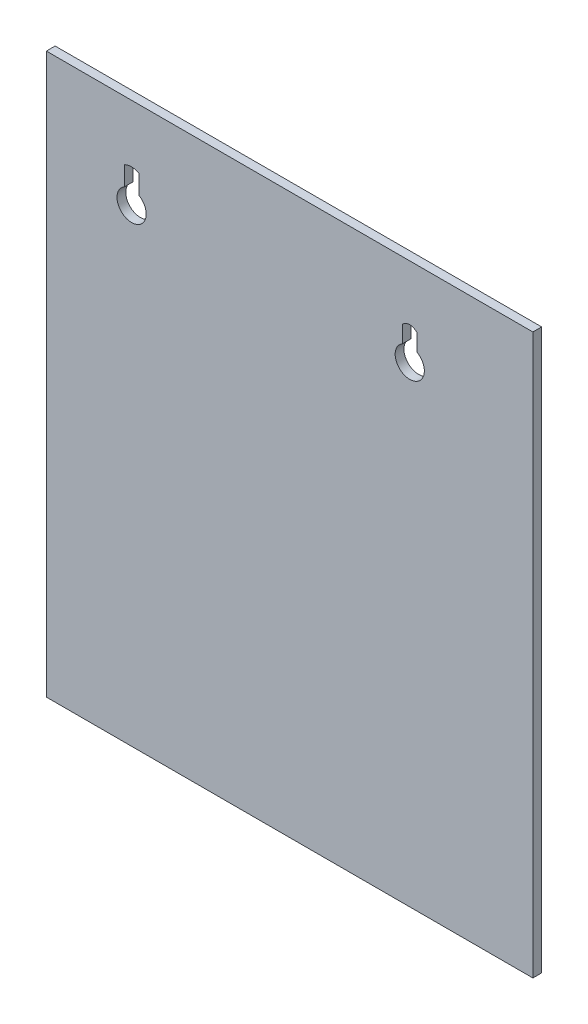
SolidWorks part; units mm, degrees
ref_plane "Ön Düzlem" through (0, 0, 0) normal (0, 0, 1) x (1, 0, 0)
ref_plane "Üst Düzlem" through (0, 0, 0) normal (0, 1, 0) x (1, 0, 0)
ref_plane "Sağ Düzlem" through (0, 0, 0) normal (1, 0, 0) x (0, 0, -1)
sketch "Çizim1" plane through (0, 0, 0) normal (0, 0, 1) x (1, 0, 0)
  line L1 (-48.9504, 24.8584) -> (51.0496, 24.8584)
  line L2 (-48.9504, 24.8584) -> (-48.9504, -90.1416)
  line L3 (-48.9504, -90.1416) -> (51.0496, -90.1416)
  line L4 (51.0496, 24.8584) -> (51.0496, -90.1416)
  dimension "D1" = 100
  dimension "D2" = 115
extrude "Yükseklik-Ekstrüzyon1" add sketch "Çizim1" along normal blind 1.8
sketch "Çizim2" plane through (0, 0, 0) normal (0, 0, 1) x (1, 0, 0)
  line L6 (-32.9284, 8.6906) -> (-32.9284, 12.654)
  line L8 (-29.9284, 8.6906) -> (-29.9284, 12.654)
  arc A0 (-32.9284, 8.6906) -> (-29.9284, 8.6906) centre (-31.4284, 6.0925) ccw
  spline S0 degree 2 poles (-32.9284, 12.654) (-31.4284, 13.3456) (-29.9284, 12.654) knots 0 0 0 1 1 1
  dimension "D1" = 6
  dimension "D2" = 3
extrude "Kes-Ekstrüzyon3" cut sketch "Çizim2" along normal blind 10
sketch "Çizim4" plane through (0, 0, 1.8) normal (0, 0, 1) x (1, 0, 0)
  line L0 (-29.9284, 12.654) -> (27.2423, 12.8568) construction
  line L6 (24.2423, 9.3554) -> (24.2423, 12.8568)
  line L8 (27.2423, 9.3554) -> (27.2423, 12.8568)
  arc A0 (24.2423, 9.3554) -> (27.2423, 9.3554) centre (25.7423, 6.7573) ccw
  spline S0 degree 2 poles (24.2423, 12.8568) (25.7423, 14.1327) (27.2423, 12.8568) knots 0 0 0 1 1 1
  dimension "D1" = 6
extrude "Kes-Ekstrüzyon5" cut sketch "Çizim4" against normal blind 10
